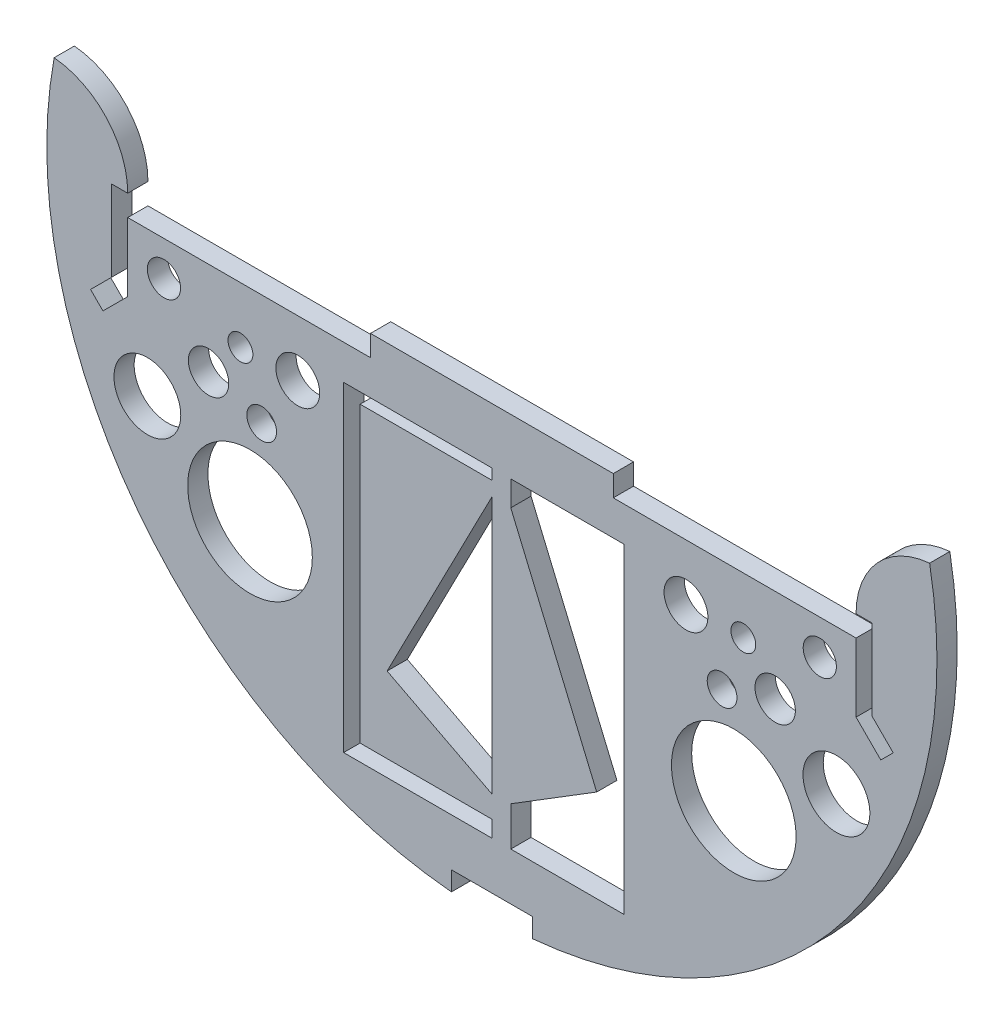
SolidWorks part; units mm, degrees
ref_plane "Front Plane" through (0, 0, 0) normal (0, 0, 1) x (1, 0, 0)
ref_plane "Top Plane" through (0, 0, 0) normal (0, 1, 0) x (1, 0, 0)
ref_plane "Right Plane" through (0, 0, 0) normal (1, 0, 0) x (0, 0, -1)
sketch "Sketch1" plane through (0, 0, 0) normal (0, 0, 1) x (1, 0, 0)
  line L0 (-140.7806, 0) -> (-82.55, 0) construction
  line L2 (-69.85, 0) -> (171.7829, 0) construction
  line L3 (-57.15, 0) -> (-59.69, 0)
  line L4 (-59.69, 0) -> (-59.69, -12.7)
  line L5 (-59.69, -12.7) -> (-62.9818, -15.9918)
  line L6 (-62.9818, -15.9918) -> (-61.0335, -17.9401)
  line L7 (-61.0335, -17.9401) -> (-57.15, -14.0565)
  line L8 (-57.15, -14.0565) -> (-57.15, -3.302)
  line L9 (-57.15, -3.302) -> (-19.05, -3.302)
  line L10 (-19.05, -3.302) -> (-19.05, 0)
  line L11 (-19.05, 0) -> (19.05, 0)
  line L12 (0, 40.3651) -> (0, -53.0706) construction
  line L13 (19.05, -3.302) -> (19.05, 0)
  line L14 (57.15, -3.302) -> (19.05, -3.302)
  line L15 (57.15, -14.0565) -> (57.15, -3.302)
  line L16 (61.0335, -17.9401) -> (57.15, -14.0565)
  line L17 (62.9818, -15.9918) -> (61.0335, -17.9401)
  line L18 (59.69, -12.7) -> (62.9818, -15.9918)
  line L19 (59.69, 0) -> (59.69, -12.7)
  line L20 (57.15, 0) -> (59.69, 0)
  line L21 (-6.35, -69.5608) -> (-6.35, -66.548)
  line L22 (0, -12.7) -> (-16.4465, -44.5882)
  line L23 (-16.4465, -44.5882) -> (0, -53.0706)
  line L24 (0, -53.0706) -> (0, -12.7)
  line L25 (16.4465, -44.5882) -> (2.9655, -52.9239)
  line L26 (2.9655, -12.7) -> (16.4465, -44.5882)
  line L27 (2.9655, -8.761) -> (20.7587, -8.761)
  line L28 (20.7587, -8.761) -> (20.7587, -59.0782)
  line L29 (20.7587, -59.0782) -> (2.9655, -59.0782)
  line L30 (2.9655, -8.761) -> (2.9655, -12.7)
  line L31 (2.9655, -52.9239) -> (2.9655, -59.0782)
  line L32 (0, -55.4212) -> (0, -83.615) construction
  line L33 (0, -59.0782) -> (-23.2688, -59.0782)
  line L34 (-23.2688, -59.0782) -> (-23.2688, -12.1075)
  line L35 (-23.2688, -12.1075) -> (-23.2688, -8.761)
  line L36 (-23.2688, -8.761) -> (0, -8.761)
  line L37 (0, -8.761) -> (0, -10.4343)
  line L38 (0, -10.4343) -> (-20.6764, -10.4343)
  line L39 (-20.6764, -10.4343) -> (-20.6764, -56.4973)
  line L40 (-20.6764, -56.4973) -> (0, -56.4973)
  line L41 (0, -56.4973) -> (0, -59.0782)
  line L42 (-6.35, -66.548) -> (6.35, -66.548)
  line L43 (6.35, -69.5608) -> (6.35, -66.548)
  arc A0 (-69.85, 0) -> (-6.35, -69.5608) centre (0, 0) ccw
  arc A1 (57.15, 0) -> (68.6955, 12.6474) centre (69.85, 0) cw
  arc A2 (-57.15, 0) -> (-68.6955, 12.6474) centre (-69.85, 0) ccw
  circle A3 centre (-51.4607, -8.761) radius 2.6078
  circle A4 centre (-54.0685, -26.0264) radius 5.2425
  circle A5 centre (-44.4601, -17.9401) radius 3.1669
  circle A6 centre (-37.9596, -35.0271) radius 9.7832
  circle A7 centre (-30.4589, -12.1075) radius 3.4391
  circle A8 centre (-36.1261, -20.7838) radius 2.3335
  circle A9 centre (-39.4597, -12.1075) radius 1.9494
  circle A10 centre (37.9596, -35.0271) radius 9.7832
  circle A11 centre (36.1261, -20.7838) radius 2.3335
  circle A12 centre (30.4589, -12.1075) radius 3.4391
  circle A13 centre (39.4597, -12.1075) radius 1.9494
  circle A14 centre (44.4601, -17.9401) radius 3.1669
  circle A15 centre (54.0685, -26.0264) radius 5.2425
  circle A16 centre (51.4607, -8.761) radius 2.6078
  arc A17 (-69.85, 0) -> (-68.6955, 12.6474) centre (0, 0) cw
  arc A18 (69.85, 0) -> (68.6955, 12.6474) centre (0, 0) ccw
  arc A19 (6.35, -69.5608) -> (69.85, 0) centre (0, 0) ccw
  point P82 (0, -66.548)
extrude "Boss-Extrude1" add sketch "Sketch1" along normal blind 3.175
